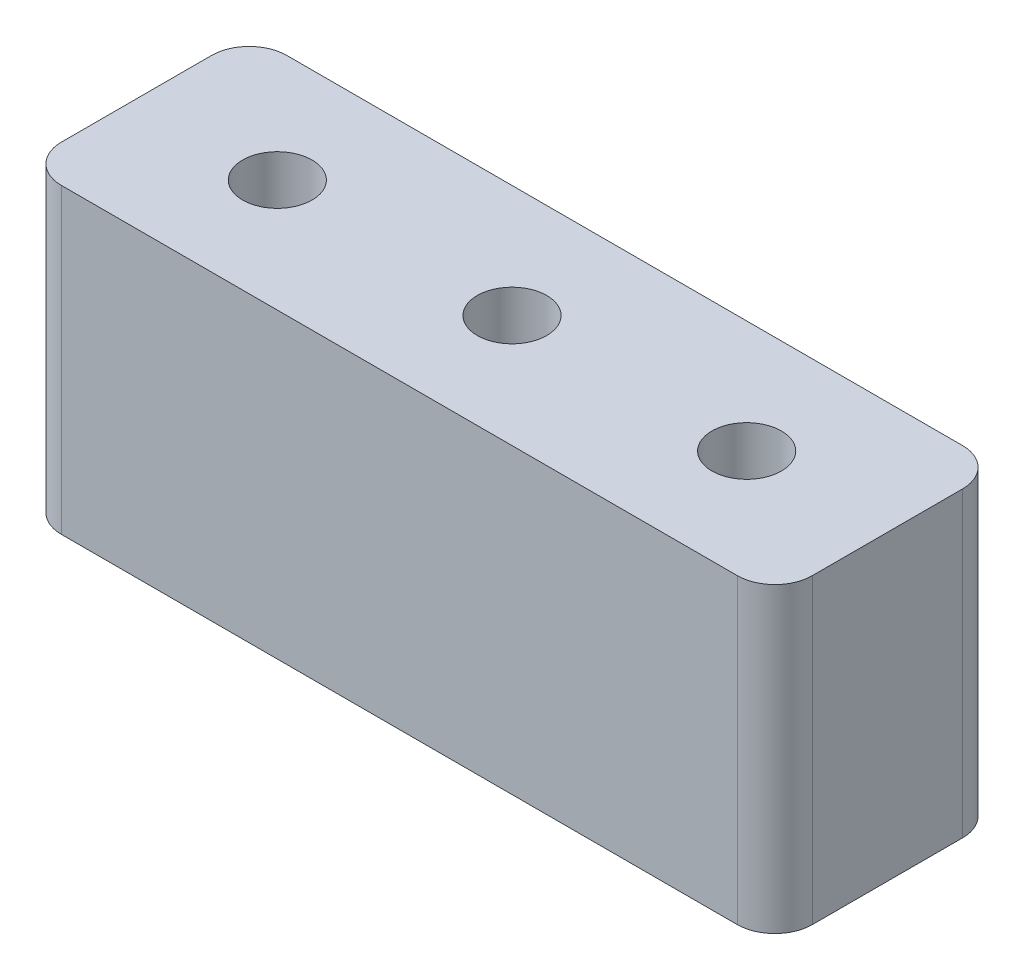
SolidWorks part; units mm, degrees
material "ABS"
ref_plane "前视基准面" through (0, 0, 0) normal (0, 0, 1) x (1, 0, 0)
ref_plane "上视基准面" through (0, 0, 0) normal (0, 1, 0) x (1, 0, 0)
ref_plane "右视基准面" through (0, 0, 0) normal (1, 0, 0) x (0, 0, -1)
other "Configuration Table"
sketch "草图1" plane through (0, 0, 0) normal (0, 1, 0) x (1, 0, 0)
  line L0 (0, -17.162) -> (0, 15.8514) construction
  line L1 (-20, 6) -> (20, 6)
  line L2 (-20, 6) -> (-20, -6)
  line L3 (-20, -6) -> (20, -6)
  line L4 (20, 6) -> (20, -6)
  line L5 (-20, 6) -> (20, -6) construction
  line L6 (-20, -6) -> (20, 6) construction
  circle A0 centre (-12.5, 0) radius 1.85
  circle A1 centre (12.5, 0) radius 1.85
  point P0 (0, 0)
  dimension "D3" = 3.7
  dimension "D1" = 40
  dimension "D2" = 12
  dimension "D4" = 25
extrude "凸台-拉伸1" add sketch "草图1" along normal blind 16.1
fillet "圆角1" radius 2 4 edges at (20, 8.05, -6) (-20, 8.05, 6) (-20, 8.05, -6) (20, 8.05, 6)
sketch "草图2" plane through (0, 16.1, 0) normal (0, 1, 0) x (1, 0, 0)
  circle A0 centre (0, 0) radius 1.85
  circle A1 centre (12.5, 0) radius 1.85 construction
extrude "切除-拉伸1" cut sketch "草图2" against normal blind 20
